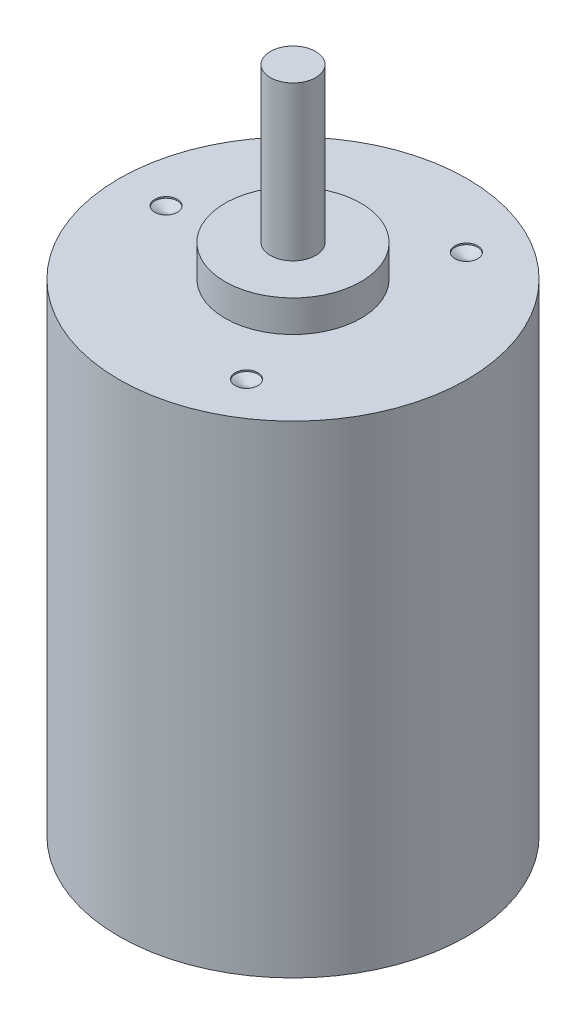
SolidWorks part; units mm, degrees
ref_plane "Front Plane" through (0, 0, 0) normal (0, 0, 1) x (1, 0, 0)
ref_plane "Top Plane" through (0, 0, 0) normal (0, 1, 0) x (1, 0, 0)
ref_plane "Right Plane" through (0, 0, 0) normal (1, 0, 0) x (0, 0, -1)
sketch "Sketch1" plane through (0, 0, 0) normal (1, 0, 0) x (0, 0, -1)
  line L0 (0, 33.9706) -> (0, -50.7941) construction
  line L1 (0, 0) -> (19.2, 0)
  line L2 (19.2, 0) -> (19.2, 53.2)
  line L3 (19.2, 53.2) -> (7.5, 53.2)
  line L7 (0, 0) -> (0, 73.7)
  line L9 (7.5, 53.2) -> (7.5, 56.7)
  line L10 (7.5, 56.7) -> (2.5, 56.7)
  line L11 (2.5, 56.7) -> (2.5, 73.7)
  line L12 (2.5, 73.7) -> (0, 73.7)
  dimension "D1" = 19.2
  dimension "D2" = 73.7
  dimension "D3" = 53.2
  dimension "D4" = 3.5
  dimension "D5" = 2.5
  dimension "D6" = 7.5
revolve "Revolve1" add sketch "Sketch1" angle 360 about L0
sketch "Sketch2" plane through (0, 53.2, 0) normal (0, 1, 0) x (1, 0, 0)
  line L0 (0, 19.2) -> (0, -19.2) construction
  line L1 (-19.2, 0) -> (19.2, 0) construction
  line L2 (0, 0) -> (7, 12.1244) construction
  circle A0 centre (0, 0) radius 19.2 construction
  circle A1 centre (0, 0) radius 14
  circle A5 centre (7, 12.1244) radius 0.551
  circle A6 centre (7, -12.1244) radius 0.551
  circle A7 centre (-14, 0) radius 0.551
  point P19 (0, 0)
  point P20 (0, 0)
  dimension "D1" = 60
  dimension "D2" = 3
hole_wizard "M3 Tapped Hole1" positions "Sketch5" profile "Sketch6" tap size "M3" standard "ISO"
sketch "Sketch5" plane through (0, 53.2, 0) normal (0, 1, 0) x (1, 0, 0)
  point P1 (7, 12.1244)
  point P4 (7, -12.1244)
  point P7 (-14, 0)
sketch "Sketch6" plane through (7, 53.2, -12.1244) normal (1, 0, 0) x (0, 0, 1)
  line L0 (0, 0) -> (0, 0.9111)
  line L1 (0, 0.9111) -> (1.25, 0.16)
  line L2 (1.25, 0.16) -> (1.25, 0)
  line L5 (1.25, 0) -> (0, 0)
  line L10 (0, 0.9111) -> (-1.25, 0.16) construction
  line L11 (0, -6.35) -> (0, 107.95) construction
  dimension "Tap Drill Dia." = 2.5
  dimension "Tap Drill Depth" = 0.16
  dimension "Drill Angle" = 118
cosmetic thread "Hole Thread1" parameters "D1"=0.12, "D2"=3
cosmetic thread "Hole Thread2" parameters "D1"=0.12, "D2"=3
cosmetic thread "Hole Thread3" parameters "D1"=0.12, "D2"=3
